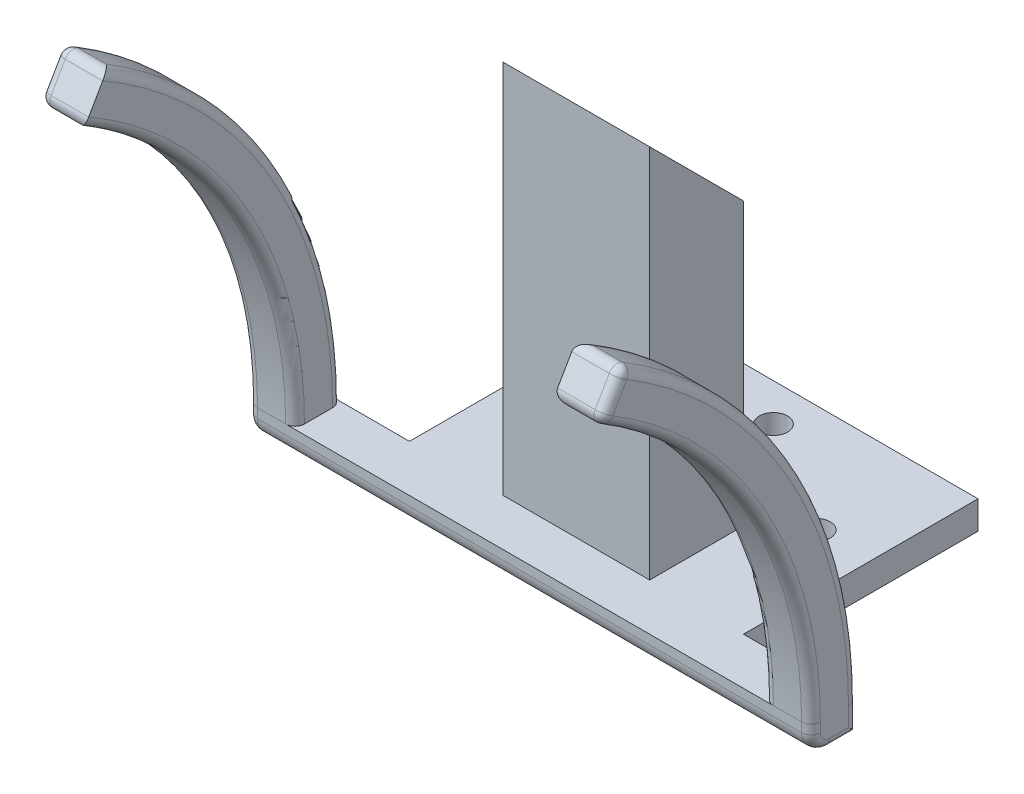
SolidWorks part; units mm, degrees
ref_plane "Front Plane" through (0, 0, 0) normal (0, 0, 1) x (1, 0, 0)
ref_plane "Top Plane" through (0, 0, 0) normal (0, 1, 0) x (1, 0, 0)
ref_plane "Right Plane" through (0, 0, 0) normal (1, 0, 0) x (0, 0, -1)
sketch "Sketch1" plane through (0, 0, 0) normal (0, 1, 0) x (1, 0, 0)
  line L0 (-8.4368, 20.25) -> (-8.4368, -4.75) construction
  line L1 (-26.2418, 20.25) -> (9.3682, 20.25)
  line L2 (-26.2418, 20.25) -> (-26.2418, -4.75)
  line L3 (-26.2418, -4.75) -> (9.3682, -4.75)
  line L4 (9.3682, 20.25) -> (9.3682, -4.75)
  line L5 (-38.4368, -4.75) -> (21.5632, -4.75)
  line L6 (-38.4368, -4.75) -> (-38.4368, -9.75)
  line L7 (-38.4368, -9.75) -> (21.5632, -9.75)
  line L8 (21.5632, -4.75) -> (21.5632, -9.75)
  point P10 (-8.4368, -4.75)
  dimension "D1" = 25
  dimension "D2" = 35.61
  dimension "D3" = 60
  dimension "D4" = 5
extrude "Boss-Extrude1" add sketch "Sketch1" along normal blind 3 contours L8 L5 L3 L6 L7 | L1 L0 L5 L4 | L0 L1 L2 L3
fillet "Fillet1" radius 2 1 edges at (-8.4368, 0, 9.75)
ref_plane "Plane1" through (21.5632, 0, 0) normal (1, 0, 0) x (0, 0, -1)
sketch "Sketch2" plane through (21.5632, 0, 0) normal (1, 0, 0) x (0, 0, -1)
  line L0 (-9.75, 3) -> (-39.75, 3) construction
  line L1 (-39.75, 3) -> (-54.75, 3) construction
  line L2 (-29.75, 46.3013) -> (-32.25, 41.9711)
  line L3 (-9.75, 3) -> (-4.75, 3)
  circle A0 centre (-54.75, 3) radius 15 construction
  arc A1 (-9.75, 3) -> (-32.25, 41.9711) centre (-54.75, 3) ccw
  arc A2 (-4.75, 3) -> (-29.75, 46.3013) centre (-54.75, 3) ccw
  dimension "D3" = 30
  dimension "D1" = 30
  dimension "D2" = 15
extrude "Boss-Extrude3" add sketch "Sketch2" against normal blind 5
ref_plane "Plane2" through (-8.4368, 0, 0) normal (1, 0, 0) x (0, 0, -1)
fillet "Fillet2" radius 1 11 edges at (16.5632, 25.5, 15.7789) (19.0632, 41.9711, 32.25) (19.0632, 46.3013, 29.75) (16.5632, 28, 11.4487) (21.5632, 25.5, 15.7789) (21.5632, 44.1362, 31) (21.5632, 28, 11.4487) (21.5632, 1.5, 4.75) (21.5632, 0, 6.25) (21.5632, 0.5858, 9.1642) (21.5632, 2.5, 9.75)
mirror "Mirror3" about plane through (-8.4368, 0, 0) normal (1, 0, 0) of "Boss-Extrude3"
fillet "Fillet3" radius 1 11 edges at (-33.4368, 28, 11.4487) (-35.9368, 46.3013, 29.75) (-35.9368, 41.9711, 32.25) (-33.4368, 25.5, 15.7789) (-38.4368, 1.5, 4.75) (-38.4368, 28, 11.4487) (-38.4368, 44.1362, 31) (-38.4368, 25.5, 15.7789) (-38.4368, 2.5, 9.75) (-38.4368, 0.5858, 9.1642) (-38.4368, 0, 6.25)
sketch "Sketch3" plane through (0, 0, 0) normal (0, -1, 0) x (1, 0, 0)
  circle A0 centre (-20.4847, -8.75) radius 1.5
  circle A1 centre (-8.4349, -16.25) radius 1.5
  circle A2 centre (3.6149, -8.75) radius 1.5
  dimension "D1" = 3
extrude "Cut-Extrude1" cut sketch "Sketch3" against normal blind 5
sketch "Sketch7" plane through (0, 3, 0) normal (0, 1, 0) x (1, 0, 0)
  line L0 (-26.2418, 20.25) -> (-26.2418, -4.75) construction
  line L1 (-16.2418, 5.25) -> (-0.6318, 5.25)
  line L2 (-16.2418, 5.25) -> (-16.2418, -4.75)
  line L3 (-16.2418, -4.75) -> (-0.6318, -4.75)
  line L4 (-0.6318, 5.25) -> (-0.6318, -4.75)
  line L5 (9.3682, 20.25) -> (9.3682, -4.75) construction
  line L6 (-38.4368, -9.75) -> (21.5632, -9.75) construction
  dimension "D1" = 10
  dimension "D2" = 10
  dimension "D3" = 5
  dimension "D4" = 10
extrude "Boss-Extrude4" add sketch "Sketch7" along normal blind 30
sketch "Sketch8" plane through (-16.2418, 0, 0) normal (-1, 0, 0) x (0, 0, 1)
  line L0 (-5.25, 33) -> (4.75, 43)
  line L1 (4.75, 33) -> (4.75, 43)
  line L2 (-5.25, 33) -> (4.75, 33) construction
  line L3 (-5.25, 33) -> (4.75, 33)
  dimension "D1" = 45
extrude "Boss-Extrude5" add sketch "Sketch8" against normal up to surface (15.61 mm away) up to face at (-0.6318, 18, -0.25)
sketch "Sketch9" plane through (0, 19.125, -19.125) normal (0, 0.7071, -0.7071) x (1, 0, 0)
  line L0 (-16.2418, -26.6933) -> (-0.6318, -26.6933) construction
  line L1 (-16.2418, -33.7643) -> (-16.2418, -19.6222) construction
  line L2 (-0.6318, -19.6222) -> (-0.6318, -33.7643) construction
  line L3 (-8.4368, -19.6222) -> (-8.4368, -33.7643) construction
  line L4 (-0.6318, -19.6222) -> (-16.2418, -19.6222) construction
  line L5 (-0.6318, -33.7643) -> (-16.2418, -33.7643) construction
  circle A0 centre (-11.4368, -26.6933) radius 1.5
  circle A1 centre (-5.4368, -26.6933) radius 1.5
  dimension "D1" = 3
  dimension "D2" = 3
  dimension "D3" = 6
  dimension "D4" = 3
extrude "Cut-Extrude2" cut sketch "Sketch9" against normal blind 5
